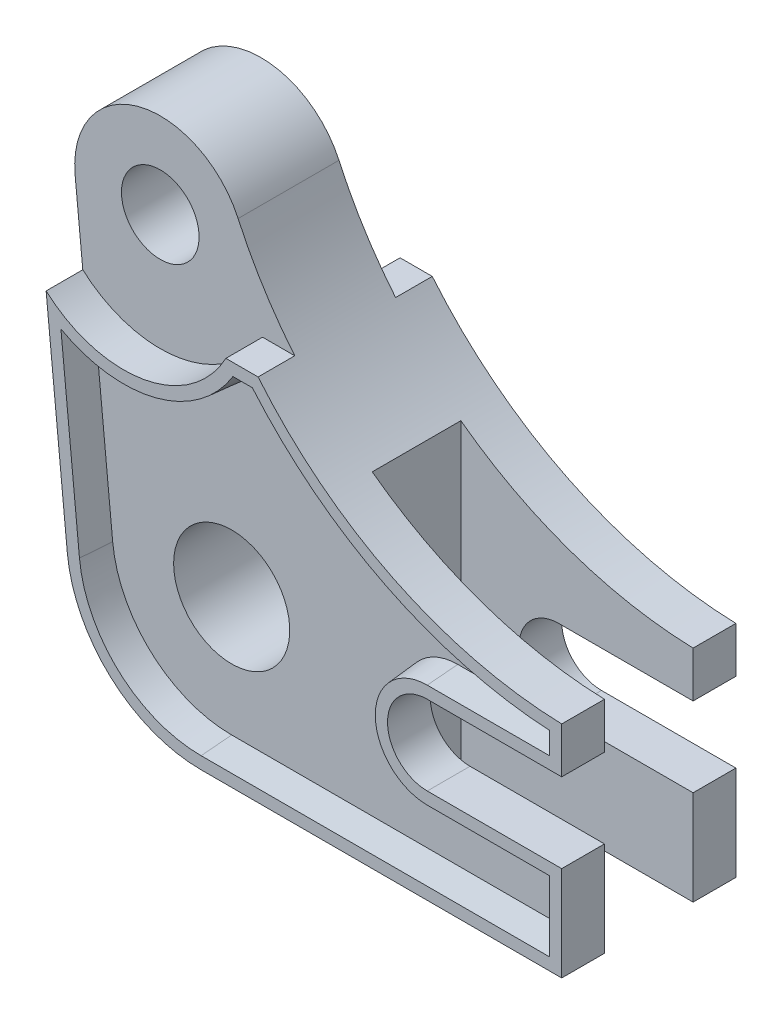
SolidWorks part; units mm, degrees
material "AISI 1020"
ref_plane "Plan de face" through (0, 0, 0) normal (0, 0, 1) x (1, 0, 0)
ref_plane "Plan de dessus" through (0, 0, 0) normal (0, 1, 0) x (1, 0, 0)
ref_plane "Plan de droite" through (0, 0, 0) normal (1, 0, 0) x (0, 0, -1)
sketch "Esquisse1" plane through (0, 0, 0) normal (0, 0, 1) x (1, 0, 0)
  line L0 (0, 0) -> (-12.6821, 47.3304) construction
  line L1 (-25.5355, 80.9701) -> (83.2336, 80.9701) construction
  line L2 (61.0021, 87.5844) -> (61.0021, -17.1484) construction
  line L3 (-26.6152, 45.9633) -> (-21.8949, -2.1482)
  line L4 (0, -22) -> (59, -22)
  line L5 (59, -22) -> (59, -6.5)
  line L6 (59, -6.5) -> (37, -6.5)
  line L7 (37, 6.5) -> (59, 6.5)
  line L8 (59, 6.5) -> (59, 14)
  line L9 (0, 0) -> (0, 31.0252) construction
  circle A0 centre (0, 0) radius 9.5
  arc A1 (-21.8949, -2.1482) -> (0, -22) centre (0, 0) ccw
  circle A2 centre (-12.6821, 47.3304) radius 6.35
  arc A3 (0.0534, 53.1446) -> (-26.6152, 45.9633) centre (-12.6821, 47.3304) ccw
  arc A4 (37, -6.5) -> (37, 6.5) centre (37, 0) cw
  arc A5 (59, 14) -> (0.0534, 53.1446) centre (61.0021, 80.9701) cw
  dimension "D3" = 14
  dimension "D4" = 22
  dimension "D7" = 12.7
  dimension "D8" = 19
  dimension "D9" = 6.5
  dimension "D11" = 67
  dimension "D1" = 59
  dimension "D2" = 36
  dimension "D5" = 15
  dimension "D6" = 49
  dimension "D10" = 22
extrude "Boss.-Extru.1" add sketch "Esquisse1" along normal mid plane 28.5
sketch "Esquisse2" plane through (0, 0, 14.25) normal (0, 0, 1) x (1, 0, 0)
  line L0 (-26.6152, 45.9633) -> (-21.8949, -2.1482) construction
  line L1 (4.0511, 38.3304) -> (9.3218, 38.3304)
  line L2 (-26.6152, 45.9633) -> (-25.361, 33.1795)
  arc A0 (-25.361, 33.1795) -> (4.0511, 38.3304) centre (-12.6821, 47.3304) ccw
  arc A1 (0.0534, 53.1446) -> (59, 14) centre (61.0021, 80.9701) ccw construction
  arc A2 (0.0534, 53.1446) -> (-26.6152, 45.9633) centre (-12.6821, 47.3304) ccw construction
  arc A3 (0.0534, 53.1446) -> (-26.6152, 45.9633) centre (-12.6821, 47.3304) ccw
  arc A4 (0.0534, 53.1446) -> (9.3218, 38.3304) centre (61.0021, 80.9701) ccw
  dimension "D1" = 19
  dimension "D2" = 9
extrude "Enlèv. mat.-Extru.1" cut sketch "Esquisse2" against normal blind 6
mirror "Symétrie1" about plane through (0, 0, 0) normal (0, 0, 1) of "Enlèv. mat.-Extru.1"
sketch "Esquisse3" plane through (0, 0, 0) normal (0, 0, 1) x (1, 0, 0)
  line L0 (21, -22) -> (21, 27.2222)
  line L1 (0, -22) -> (59, -22) construction
  line L2 (59, -22) -> (59, -6.5) construction
  line L3 (21, -22) -> (59, -22)
  line L4 (59, -22) -> (59, 14)
  arc A0 (9.3218, 38.3304) -> (59, 14) centre (61.0021, 80.9701) ccw construction
  arc A1 (21, 27.2222) -> (59, 14) centre (61.0021, 80.9701) ccw
  dimension "D1" = 38
extrude "Enlèv. mat.-Extru.2" cut sketch "Esquisse3" along normal offset from surface 7 and the other way offset from surface (7.25 mm away) 7 up to face at (24.0372, 5.542, 14.25) other way up to face at (9.5, 0, -14.25)
sketch "Esquisse4" plane through (0, 0, 14.25) normal (0, 0, 1) x (1, 0, 0)
  line L14 (8.3875, 36.3304) -> (5.2064, 36.3304)
  line L15 (-22.942, 29.0073) -> (-19.9044, -1.9529)
  line L16 (0, -20) -> (57, -20)
  line L17 (57, -20) -> (57, -8.5)
  line L18 (57, -8.5) -> (37, -8.5)
  line L19 (37, 8.5) -> (57, 8.5)
  line L20 (57, 8.5) -> (57, 12.0862)
  line L21 (8.3875, 36.3304) -> (5.2064, 36.3304)
  line L22 (-22.942, 29.0073) -> (-19.9044, -1.9529)
  line L23 (0, -20) -> (57, -20)
  line L24 (57, -20) -> (57, -8.5)
  line L25 (57, -8.5) -> (37, -8.5)
  line L26 (37, 8.5) -> (57, 8.5)
  line L27 (57, 8.5) -> (57, 12.0862)
  arc A8 (-22.942, 29.0073) -> (5.2064, 36.3304) centre (-12.6821, 47.3304) ccw
  arc A9 (-19.9044, -1.9529) -> (0, -20) centre (0, 0) ccw
  arc A10 (37, 8.5) -> (37, -8.5) centre (37, 0) ccw
  arc A11 (8.3875, 36.3304) -> (57, 12.0862) centre (61.0021, 80.9701) ccw
  arc A12 (-22.942, 29.0073) -> (5.2064, 36.3304) centre (-12.6821, 47.3304) ccw
  arc A13 (-19.9044, -1.9529) -> (0, -20) centre (0, 0) ccw
  arc A14 (37, 8.5) -> (37, -8.5) centre (37, 0) ccw
  arc A15 (8.3875, 36.3304) -> (57, 12.0862) centre (61.0021, 80.9701) ccw
  dimension "D1" = 2
extrude "Enlèv. mat.-Extru.3" cut sketch "Esquisse4" against normal offset from surface 2 draft 5
equation "\"A\"= 59"
equation "\"B\"= 22"
equation "\"C\"= 28.5"
equation "\"D1@Esquisse1\"=\"A\""
equation "\"D4@Esquisse1\"=\"B\""
equation "\"D1@Boss.-Extru.1\"=\"C\""
